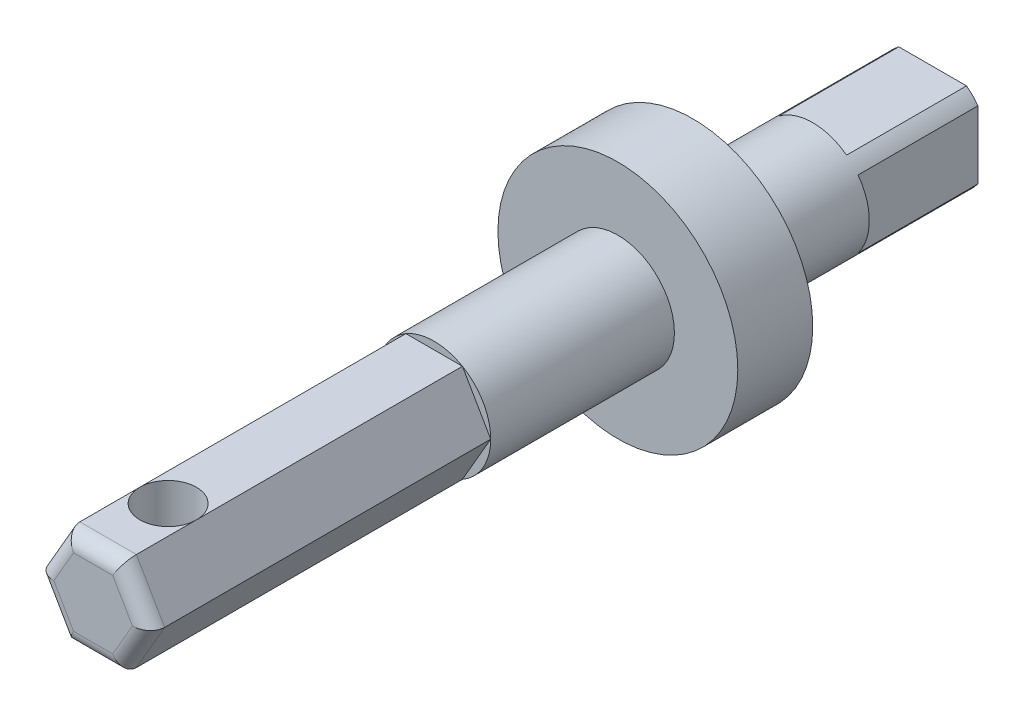
SolidWorks part; units mm, degrees
ref_plane "Front Plane" through (0, 0, 0) normal (0, 0, 1) x (1, 0, 0)
ref_plane "Top Plane" through (0, 0, 0) normal (0, 1, 0) x (1, 0, 0)
ref_plane "Right Plane" through (0, 0, 0) normal (1, 0, 0) x (0, 0, -1)
sketch "Sketch1" plane through (0, 0, 0) normal (0, 0, 1) x (1, 0, 0)
  line L0 (0, 0) -> (0, 50000) construction
  line L1 (-1000, 0) -> (3.773, 0) construction
  line L2 (-2.2577, 3.023) -> (2.2577, 3.023)
  line L3 (3.023, -2.2577) -> (3.023, 2.2577)
  line L4 (-2.8927, -0.2057) -> (0.2057, 2.8927)
  line L5 (-0.2057, -2.8927) -> (2.8927, 0.2057)
  arc A0 (-2.2577, 3.023) -> (3.023, -2.2577) centre (0, 0) ccw
  arc A1 (3.023, 2.2577) -> (2.2577, 3.023) centre (0, 0) ccw
  arc A2 (-2.8927, -0.2057) -> (-0.2057, -2.8927) centre (0, 0) ccw
  arc A3 (2.8927, 0.2057) -> (0.2057, 2.8927) centre (0, 0) ccw
  point P3 (0, 3.773)
  point P10 (0, 3.023)
  point P13 (3.023, 0)
  dimension "D1" = 7.546
  dimension "D3" = 5.8
  dimension "D2" = 0.75
  dimension "D4" = 3.8
  dimension "D5" = 45
extrude "Boss-Extrude1" add sketch "Sketch1" along normal blind 8.25
sketch "Sketch2" plane through (0, 0, 8.25) normal (0, 0, 1) x (1, 0, 0)
  line L2 (2.2577, 3.023) -> (-2.2577, 3.023)
  line L3 (3.023, -2.2577) -> (3.023, 2.2577)
  line L4 (2.2577, 3.023) -> (-2.2577, 3.023)
  line L5 (3.023, -2.2577) -> (3.023, 2.2577)
  arc A2 (3.023, 2.2577) -> (2.2577, 3.023) centre (0, 0) ccw
  arc A3 (-2.2577, 3.023) -> (3.023, -2.2577) centre (0, 0) ccw
  arc A4 (3.023, 2.2577) -> (2.2577, 3.023) centre (0, 0) ccw
  arc A5 (-2.2577, 3.023) -> (3.023, -2.2577) centre (0, 0) ccw
  dimension "D1" = 0
extrude "Boss-Extrude2" add sketch "Sketch2" along normal blind 7.75
sketch "Sketch3" plane through (0, 0, 16) normal (0, 0, 1) x (1, 0, 0)
  circle A0 centre (0, 0) radius 3.773
extrude "Boss-Extrude3" add sketch "Sketch3" against normal blind 8
sketch "Sketch5" plane through (0, 0, 16) normal (0, 0, 1) x (1, 0, 0)
  line L1 (1.8865, 3.2675) -> (-1.8865, 3.2675)
  line L2 (-1.8865, 3.2675) -> (-3.773, 0)
  line L3 (-3.773, 0) -> (-1.8865, -3.2675)
  line L4 (-1.8865, -3.2675) -> (1.8865, -3.2675)
  line L5 (1.8865, -3.2675) -> (3.773, 0)
  line L6 (3.773, 0) -> (1.8865, 3.2675)
  circle A0 centre (0, 0) radius 3.2675 construction
extrude "Boss-Extrude4" add sketch "Sketch5" along normal blind 30
sketch "Sketch6" plane through (0, 0, 16) normal (0, 0, 1) x (1, 0, 0)
  circle A0 centre (0, 0) radius 3.773
extrude "Boss-Extrude5" add sketch "Sketch6" along normal blind 10
sketch "Sketch7" plane through (0, 0, 26) normal (0, 0, 1) x (1, 0, 0)
  circle A0 centre (0, 0) radius 3.773
extrude "Boss-Extrude6" add sketch "Sketch7" along normal blind 7.254
sketch "Sketch8" plane through (0, 0, 46) normal (0, 0, 1) x (1, 0, 0)
  line L6 (3.773, 0) -> (1.8865, 3.2675)
  line L7 (1.8865, 3.2675) -> (-1.8865, 3.2675)
  line L8 (-1.8865, 3.2675) -> (-3.773, 0)
  line L9 (-3.773, 0) -> (-1.8865, -3.2675)
  line L10 (-1.8865, -3.2675) -> (1.8865, -3.2675)
  line L11 (1.8865, -3.2675) -> (3.773, 0)
  line L12 (3.773, 0) -> (1.8865, 3.2675)
  line L13 (1.8865, 3.2675) -> (-1.8865, 3.2675)
  line L14 (-1.8865, 3.2675) -> (-3.773, 0)
  line L15 (-3.773, 0) -> (-1.8865, -3.2675)
  line L16 (-1.8865, -3.2675) -> (1.8865, -3.2675)
  line L17 (1.8865, -3.2675) -> (3.773, 0)
  dimension "D1" = 0
extrude "Boss-Extrude7" add sketch "Sketch8" along normal blind 10
ref_plane "Plane1" through (0, 0, 21) normal (0, 0, 1) x (1, 0, 0)
sketch "Sketch9" plane through (0, 0, 21) normal (0, 0, 1) x (1, 0, 0)
  circle A0 centre (0, 0) radius 8
  dimension "D1" = 16
extrude "Boss-Extrude8" add sketch "Sketch9" against normal blind 5
sketch "Sketch10" plane through (0, 3.2675, 0) normal (0, 1, 0) x (1, 0, 0)
  line L0 (1.8865, -56) -> (-1.8865, -56) construction
  circle A0 centre (0, -51) radius 1.8865
  dimension "D1" = 5
extrude "Cut-Extrude1" cut sketch "Sketch10" against normal through all
fillet "Fillet1" radius 1 6 edges at (2.8297, -1.6338, 56) (2.8297, 1.6338, 56) (0, 3.2675, 56) (-2.8297, 1.6338, 56) (-2.8297, -1.6338, 56) (0, -3.2675, 56)
